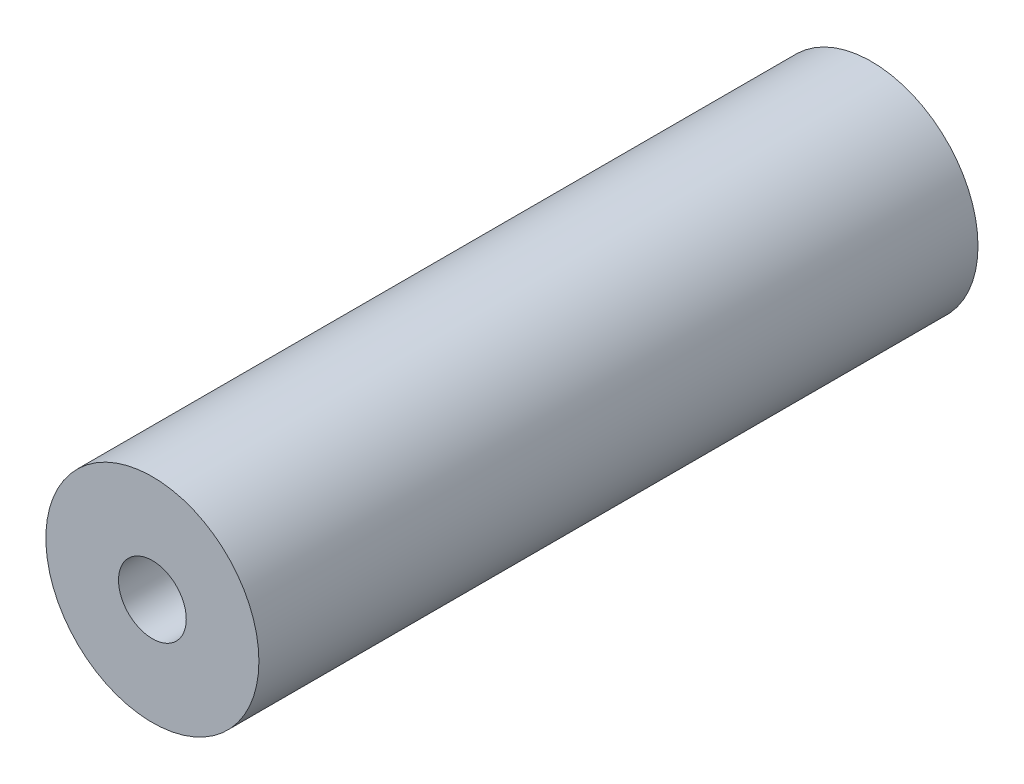
SolidWorks part; units mm, degrees
material "6061-T6 (SS)"
ref_plane "Front Plane" through (0, 0, 0) normal (0, 0, 1) x (1, 0, 0)
ref_plane "Top Plane" through (0, 0, 0) normal (0, 1, 0) x (1, 0, 0)
ref_plane "Right Plane" through (0, 0, 0) normal (1, 0, 0) x (0, 0, -1)
sketch "Sketch1" plane through (0, 0, 0) normal (0, 0, 1) x (1, 0, 0)
  circle A1 centre (0, 0) radius 6.35
  dimension "D2" = 12.7
extrude "Boss-Extrude1" add sketch "Sketch1" along normal mid plane 42.8625
hole_wizard "#10-32 Tapped Hole1" positions "3DSketch1" profile "Sketch2" tap size "#10-32" standard "ANSI Inch"
sketch3d "3DSketch1"
  line L0 (0, 0, 21.4312) -> (0, 0, -21.4312) construction
  point P0 (0, 0, 21.4312)
  point P4 (0, 0, -21.4312)
sketch "Sketch2" plane through (0, 0, 21.4312) normal (1, 0, 0) x (0, -1, 0)
  line L0 (0, 0) -> (0, 13.2428)
  line L1 (0, 13.2428) -> (2.0193, 12.0294)
  line L2 (2.0193, 12.0294) -> (2.0193, 0)
  line L5 (2.0193, 0) -> (0, 0)
  line L10 (0, 13.2428) -> (-2.0193, 12.0294) construction
  line L11 (0, -6.35) -> (0, 107.95) construction
  dimension "Tap Drill Dia." = 4.0386
  dimension "Tap Drill Depth" = 12.0294
  dimension "Drill Angle" = 118
cosmetic thread "Hole Thread1"
cosmetic thread "Hole Thread2"
